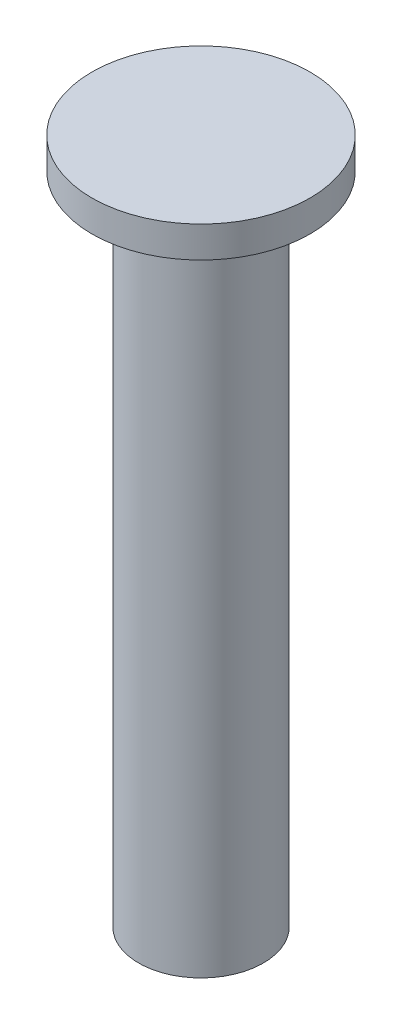
SolidWorks part; units mm, degrees
ref_plane "Front Plane" through (0, 0, 0) normal (0, 0, 1) x (1, 0, 0)
ref_plane "Top Plane" through (0, 0, 0) normal (0, 1, 0) x (1, 0, 0)
ref_plane "Right Plane" through (0, 0, 0) normal (1, 0, 0) x (0, 0, -1)
sketch "Sketch1" plane through (0, 0, 0) normal (0, 1, 0) x (1, 0, 0)
  circle A0 centre (0, 0) radius 2
  dimension "D1" = 4
extrude "Boss-Extrude1" add sketch "Sketch1" along normal blind 21
sketch "Sketch2" plane through (0, 21, 0) normal (0, 1, 0) x (1, 0, 0)
  circle A0 centre (0, 0) radius 3.5
  dimension "D1" = 7
extrude "Boss-Extrude2" add sketch "Sketch2" along normal blind 1
